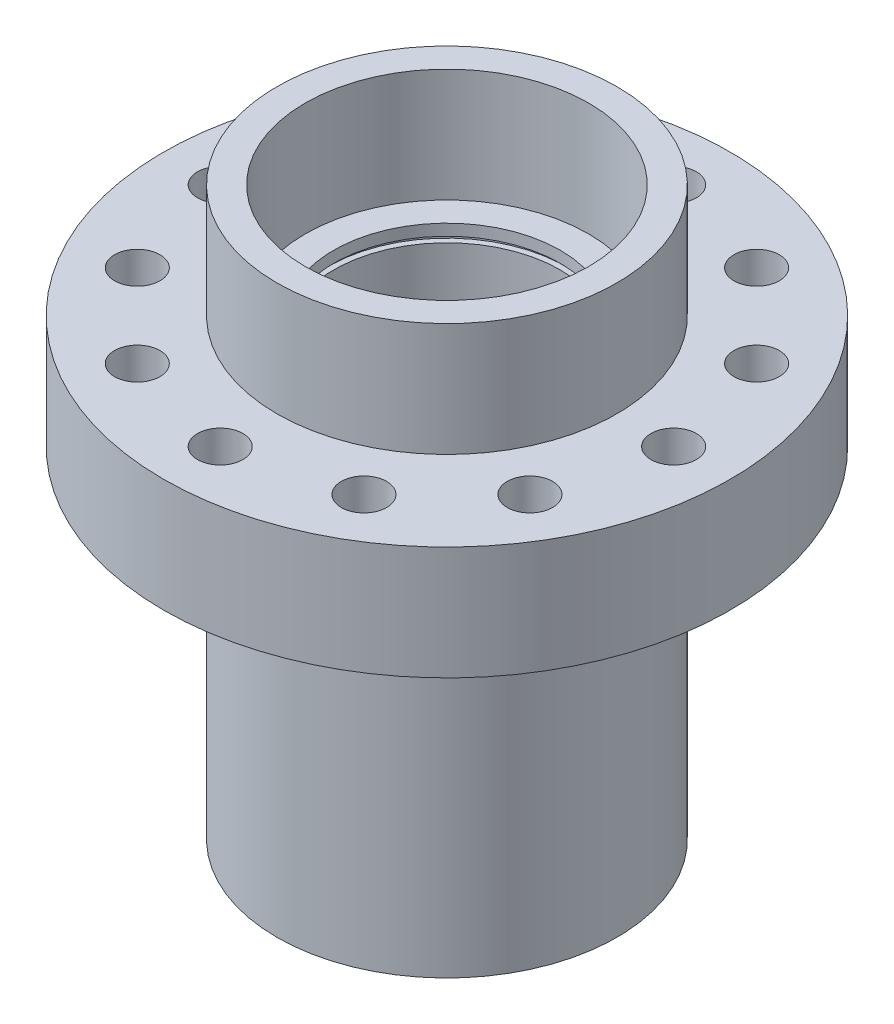
SolidWorks part; units mm, degrees
ref_plane "Ön Düzlem" through (0, 0, 0) normal (0, 0, 1) x (1, 0, 0)
ref_plane "Üst Düzlem" through (0, 0, 0) normal (0, 1, 0) x (1, 0, 0)
ref_plane "Sağ Düzlem" through (0, 0, 0) normal (1, 0, 0) x (0, 0, -1)
sketch "Sketch1" plane through (0, 0, 0) normal (0, 0, 1) x (1, 0, 0)
  line L0 (20, 80) -> (50, 80)
  line L1 (50, 80) -> (50, 60)
  line L2 (30, 0) -> (0, 0)
  line L3 (0, 80) -> (0, 0) construction
  line L4 (10, 65) -> (10, 15)
  line L5 (50, 60) -> (30, 60)
  line L6 (30, 60) -> (30, 0)
  line L7 (20, 80) -> (20, 78)
  line L8 (20, 65) -> (10, 65)
  line L9 (20, 0) -> (20, 2)
  line L10 (20, 15) -> (10, 15)
  line L11 (20, 3) -> (21, 3)
  line L12 (21, 3) -> (21, 2)
  line L13 (21, 2) -> (20, 2)
  line L14 (10, 40) -> (54.5746, 40) construction
  line L15 (20, 77) -> (21, 77)
  line L16 (21, 77) -> (21, 78)
  line L17 (21, 78) -> (20, 78)
  line L18 (20, 77) -> (20, 65)
  line L19 (20, 3) -> (20, 15)
  point P7 (20, 3)
  point P8 (20, 77)
  dimension "D1" = 80
  dimension "D2" = 50
  dimension "D3" = 10
  dimension "D4" = 30
  dimension "D5" = 20
  dimension "D6" = 15
  dimension "D7" = 15
  dimension "D8" = 20
  dimension "D9" = 3
  dimension "D10" = 3
  dimension "D11" = 1
  dimension "D12" = 1
revolve "Revolve1" add sketch "Sketch1" angle 360 about L3
sketch "Sketch2" plane through (0, 60, 0) normal (0, -1, 0) x (1, 0, 0)
  circle A0 centre (0, 40) radius 4
  circle A1 centre (0, 0) radius 40 construction
  circle A2 centre (20, 34.641) radius 4
  circle A3 centre (34.641, 20) radius 4
  circle A4 centre (40, 0) radius 4
  circle A5 centre (34.641, -20) radius 4
  circle A6 centre (20, -34.641) radius 4
  circle A7 centre (0, -40) radius 4
  circle A8 centre (-20, -34.641) radius 4
  circle A9 centre (-34.641, -20) radius 4
  circle A10 centre (-40, 0) radius 4
  circle A11 centre (-34.641, 20) radius 4
  circle A12 centre (-20, 34.641) radius 4
  point P29 (0, 0)
  dimension "D1" = 8
  dimension "D2" = 80
  dimension "D3" = 12
extrude "Cut-Extrude1" cut sketch "Sketch2" against normal up to surface (20 mm away) up to face at (0, 80, 50)
sketch "Sketch3" plane through (0, 80, 0) normal (0, 1, 0) x (1, 0, 0)
  circle A0 centre (0, 0) radius 30
  dimension "D1" = 60
extrude "Extrude-Thin1" add sketch "Sketch3" along normal blind 20 thin thin type one direction reverse wall 5
